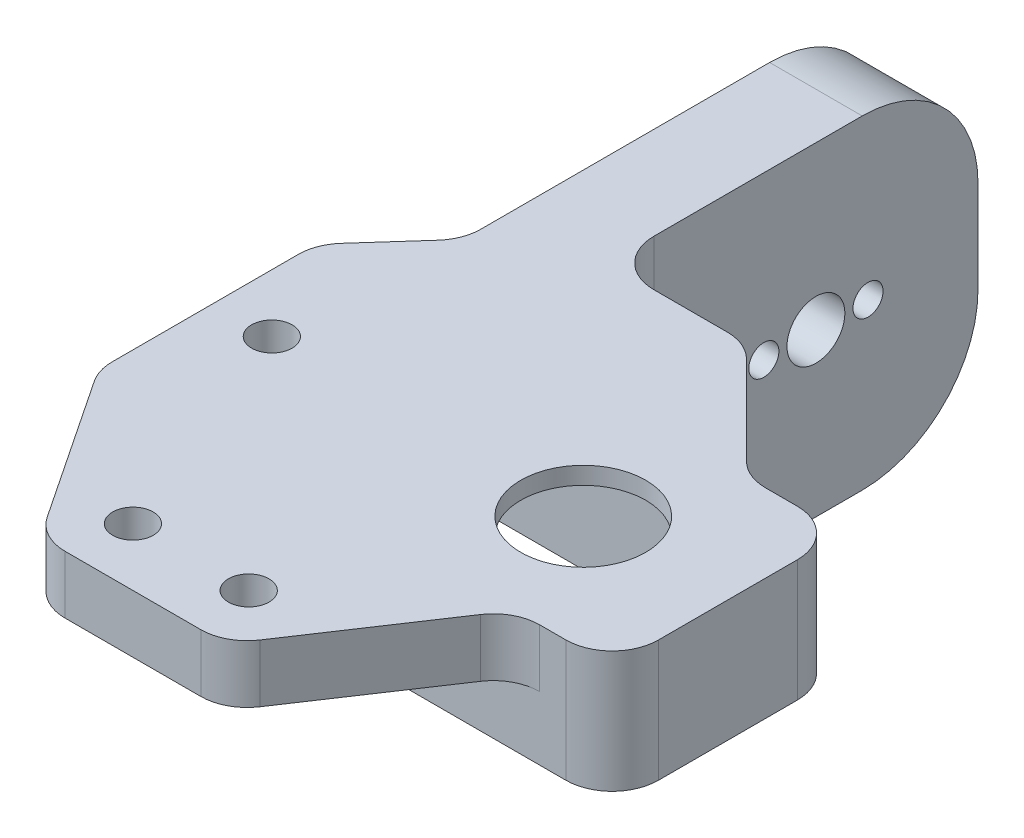
SolidWorks part; units mm, degrees
ref_plane "Front Plane" through (0, 0, 0) normal (0, 0, 1) x (1, 0, 0)
ref_plane "Top Plane" through (0, 0, 0) normal (0, 1, 0) x (1, 0, 0)
ref_plane "Right Plane" through (0, 0, 0) normal (1, 0, 0) x (0, 0, -1)
ref_plane "Plane1" through (44.4, 0, 0) normal (1, 0, 0) x (0, 0, -1)
sketch "Sketch1" plane through (44.4, 0, 0) normal (1, 0, 0) x (0, 0, -1)
  line L0 (50, -5.5) -> (35, -5.5)
  line L1 (35, -5.5) -> (50, -23)
  line L2 (50, -23) -> (50, -5.5)
extrude "Boss-Extrude1" add sketch "Sketch1" against normal blind 38.4
sketch "Sketch2" plane through (0, -5.5, 0) normal (0, 1, 0) x (-1, 0, 0)
  line L0 (-6, -50) -> (-44.4, -50)
  line L1 (-44.4, -50) -> (-44.4, -35)
  line L2 (-44.4, -35) -> (-6, -35)
  line L3 (-6, -35) -> (-6, -50)
extrude "Boss-Extrude2" add sketch "Sketch2" along normal blind 5.5
sketch "Sketch3" plane through (0, 0, -50) normal (0, 0, -1) x (-1, 0, 0)
  line L0 (-44.4, 0) -> (-6, 0)
  line L1 (-6, 0) -> (-6, -23)
  line L2 (-6, -23) -> (-44.4, -23)
  line L3 (-44.4, -23) -> (-44.4, 0)
extrude "Boss-Extrude3" add sketch "Sketch3" along normal blind 27
ref_plane "Plane2" through (0, 0, -35) normal (0, 0, 1) x (1, 0, 0)
sketch "Sketch8" plane through (0, 0, -35) normal (0, 0, 1) x (1, 0, 0)
  line L0 (44.4, 0) -> (44.4, -5.5)
  line L1 (44.4, -5.5) -> (6, -5.5)
  line L2 (6, -5.5) -> (6, 0)
  line L3 (6, 0) -> (44.4, 0)
extrude "Boss-Extrude4" add sketch "Sketch8" along normal blind 20
sketch "Sketch9" plane through (44.4, 0, 0) normal (1, 0, 0) x (0, 0, -1)
  line L0 (77, -23) -> (77, -5.5)
  line L1 (77, -5.5) -> (35, -5.5)
  line L2 (35, -5.5) -> (50, -23)
  line L3 (50, -23) -> (77, -23)
extrude "Cut-Extrude1" cut sketch "Sketch9" against normal blind 30.4
sketch "Sketch10" plane through (0, 0, -77) normal (0, 0, -1) x (-1, 0, 0)
  line L0 (-14, -5.5) -> (-14, 0)
  line L1 (-14, 0) -> (-44.4, 0)
  line L2 (-44.4, 0) -> (-44.4, -5.5)
  line L3 (-44.4, -5.5) -> (-14, -5.5)
extrude "Cut-Extrude2" cut sketch "Sketch10" against normal blind 32
sketch "Sketch11" plane through (0, 0, 0) normal (0, 1, 0) x (-1, 0, 0)
  line L0 (-10, 0) -> (0, -15)
  line L1 (0, -15) -> (0, -33.8197)
  line L2 (0, -33.8197) -> (-6, -40.5279)
  line L3 (-6, -40.5279) -> (-6, -77)
  line L4 (-6, -77) -> (-14, -77)
  line L5 (-14, -77) -> (-14, -45)
  line L6 (-14, -45) -> (-44.4, -45)
  line L7 (-44.4, -45) -> (-44.4, -15)
  line L8 (-44.4, -15) -> (-36, -15)
  line L9 (-36, -15) -> (-26, 0)
  line L10 (-26, 0) -> (-10, 0)
extrude "Boss-Extrude5" add sketch "Sketch11" along normal blind 5
ref_plane "Plane3" through (9.4, 0, 0) normal (1, 0, 0) x (0, 0, -1)
sketch "Sketch17" plane through (9.4, 0, 0) normal (1, 0, 0) x (0, 0, -1)
  line L0 (15, -5.5) -> (31.0453, -5.5)
  line L1 (31.0453, -5.5) -> (31.0453, 0)
  line L2 (31.0453, 0) -> (15, 0)
  line L3 (15, 0) -> (15, -5.5)
ref_plane "Plane4" through (6, 0, 0) normal (-1, 0, 0) x (0, 0, 1)
extrude "Cut-Extrude3" cut sketch "Sketch17" against normal up to surface (3.4 mm away) up to plane "Plane4"
sketch "Sketch24" plane through (0, 5, 0) normal (0, 1, 0) x (-1, 0, 0)
  line L0 (-36, -35) -> (-44.4, -35)
  line L1 (-44.4, -35) -> (-44.4, -45)
  line L2 (-44.4, -45) -> (-26, -45)
  line L3 (-26, -45) -> (-36, -35)
extrude "Cut-Extrude4" cut sketch "Sketch24" against normal through all
sketch "Sketch25" plane through (0, -5.5, 0) normal (0, -1, 0) x (1, 0, 0)
  line L0 (36, -35) -> (14, -35)
  line L1 (14, -35) -> (14, -45)
  line L2 (14, -45) -> (26, -45)
  line L3 (26, -45) -> (36, -35)
extrude "Cut-Extrude5" cut sketch "Sketch25" against normal blind 5.5
sketch "Sketch33" plane through (6, 0, 0) normal (-1, 0, 0) x (0, 0, 1)
  line L0 (-66.5, -12.5) -> (-59.5, -12.5)
  line L1 (-59.5, -5.5) -> (-66.5, -5.5)
  arc A0 (-66.5, -5.5) -> (-66.5, -12.5) centre (-66.5, -9) ccw
  arc A1 (-59.5, -12.5) -> (-59.5, -5.5) centre (-59.5, -9) ccw
extrude "Cut-Extrude6" cut sketch "Sketch33" against normal blind 3
sketch "Sketch34" plane through (0, -5.5, 0) normal (0, -1, 0) x (1, 0, 0)
  line L0 (15.4, -31.5) -> (38.4, -31.5)
  line L1 (38.4, -31.5) -> (38.4, -18.5)
  line L2 (38.4, -18.5) -> (15.4, -18.5)
  line L3 (15.4, -18.5) -> (15.4, -31.5)
extrude "Cut-Extrude7" cut sketch "Sketch34" against normal blind 9
hole_wizard "Ø3.5 (3.5) Diameter Hole1" positions "Sketch36" profile "Sketch35" hole size "Ø3.5" standard "ANSI Metric"
sketch "Sketch36" plane through (0, 0, 0) normal (0, -1, 0) x (-1, 0, 0)
  point P0 (-5, 25)
  point P1 (-13, 5)
  point P2 (-23, 5)
sketch "Sketch35" plane through (5, 0, -25) normal (1, 0, 0) x (0, 0, -1)
  line L0 (0, 0) -> (0, 5)
  line L1 (0, 5) -> (1.75, 5)
  line L2 (1.75, 5) -> (1.75, 0)
  line L5 (1.75, 0) -> (0, 0)
  line L11 (0, -6.35) -> (0, 107.95) construction
  dimension "Thru Hole Dia." = 3.5
  dimension "Thru Hole Depth" = 5
hole_wizard "Ø10.8 (10.8) Diameter Hole1" positions "Sketch38" profile "Sketch37" hole size "Ø10.8" standard "ANSI Metric"
sketch "Sketch38" plane through (0, 3.5, 0) normal (0, -1, 0) x (-1, 0, 0)
  point P0 (-31.9, 25)
sketch "Sketch37" plane through (31.9, 3.5, -25) normal (1, 0, 0) x (0, 0, -1)
  line L0 (0, 0) -> (0, 1.5)
  line L1 (0, 1.5) -> (5.4, 1.5)
  line L2 (5.4, 1.5) -> (5.4, 0)
  line L5 (5.4, 0) -> (0, 0)
  line L11 (0, -6.35) -> (0, 107.95) construction
  dimension "Thru Hole Dia." = 10.8
  dimension "Thru Hole Depth" = 1.5
hole_wizard "Ø5.0 (5) Diameter Hole1" positions "Sketch40" profile "Sketch39" hole size "Ø5.0" standard "ANSI Metric"
sketch "Sketch40" plane through (9, 0, 0) normal (-1, 0, 0) x (0, 0, 1)
  point P0 (-63, -9)
sketch "Sketch39" plane through (9, -9, -63) normal (0, 1, 0) x (0, 0, 1)
  line L0 (0, 0) -> (0, 35.4)
  line L1 (0, 35.4) -> (2.5, 35.4)
  line L2 (2.5, 35.4) -> (2.5, 0)
  line L5 (2.5, 0) -> (0, 0)
  line L11 (0, -6.35) -> (0, 107.95) construction
  dimension "Thru Hole Dia." = 5
  dimension "Thru Hole Depth" = 35.4
hole_wizard "Ø2.6 (2.6) Diameter Hole1" positions "Sketch42" profile "Sketch41" hole size "Ø2.6" standard "ANSI Metric"
sketch "Sketch42" plane through (14, 0, 0) normal (1, 0, 0) x (0, 0, -1)
  point P0 (58.5, -9)
  point P1 (67.5, -9)
sketch "Sketch41" plane through (14, -9, -58.5) normal (0, 1, 0) x (0, 0, -1)
  line L0 (0, 0) -> (0, 14)
  line L1 (0, 14) -> (1.3, 14)
  line L2 (1.3, 14) -> (1.3, 0)
  line L5 (1.3, 0) -> (0, 0)
  line L11 (0, -6.35) -> (0, 107.95) construction
  dimension "Thru Hole Dia." = 2.6
  dimension "Thru Hole Depth" = 14
hole_wizard "Ø2.0 (2) Diameter Hole1" positions "Sketch44" profile "Sketch43" hole size "Ø2.0" standard "ANSI Metric"
sketch "Sketch44" plane through (0, -5.5, 0) normal (0, -1, 0) x (-1, 0, 0)
  point P0 (-13.1, 25)
  point P1 (-40.7, 25)
sketch "Sketch43" plane through (13.1, -5.5, -25) normal (1, 0, 0) x (0, 0, -1)
  line L0 (0, 0) -> (0, 7)
  line L1 (0, 7) -> (1, 7)
  line L2 (1, 7) -> (1, 0)
  line L5 (1, 0) -> (0, 0)
  line L10 (0, 7) -> (-1, 7) construction
  line L11 (0, -6.35) -> (0, 107.95) construction
  dimension "Hole Dia." = 2
  dimension "Hole Depth" = 7
  dimension "Drill Angle" = 180
fillet "Fillet1" radius 4 14 edges at (36, 2.5, -35) (10, 2.5, 0) (14, 2.5, -45) (14, -2.75, -35) (14, 0, -40) (44.4, -0.25, -35) (26, 2.5, -45) (0, 2.5, -33.8197) (6, 2.5, -40.5279) (26, 2.5, 0) (0, 2.5, -15) (36, 2.5, -15) (9.4, -2.75, -15) (44.4, -0.25, -15)
fillet "Fillet2" radius 8 1 edges at (10, -23, -50)
fillet "Fillet3" radius 10 2 edges at (10, -23, -77) (10, 5, -77)
